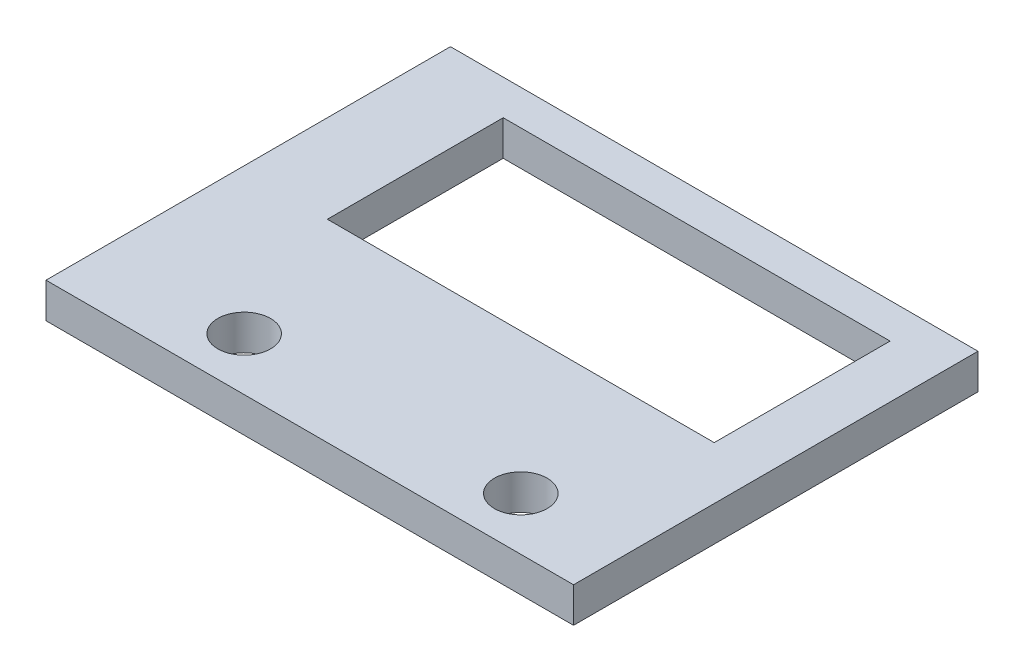
SolidWorks part; units mm, degrees
material "Perspex (TM) GS Acrylic Cast Sheet"
ref_plane "Front Plane" through (0, 0, 0) normal (0, 0, 1) x (1, 0, 0)
ref_plane "Top Plane" through (0, 0, 0) normal (0, 1, 0) x (1, 0, 0)
ref_plane "Right Plane" through (0, 0, 0) normal (1, 0, 0) x (0, 0, -1)
sketch "Sketch1" plane through (0, 0, 0) normal (0, 1, 0) x (1, 0, 0)
  line L1 (15, -11.5) -> (-15, -11.5)
  line L2 (15, -11.5) -> (15, 11.5)
  line L3 (15, 11.5) -> (-15, 11.5)
  line L4 (-15, -11.5) -> (-15, 11.5)
  line L5 (15, -11.5) -> (-15, 11.5) construction
  line L6 (15, 11.5) -> (-15, -11.5) construction
  point P0 (0, 0)
  dimension "D1" = 23
  dimension "D2" = 30
extrude "Boss-Extrude1" add sketch "Sketch1" along normal blind 2
sketch "Sketch3" plane through (0, 2, 0) normal (0, 1, 0) x (1, 0, 0)
  line L1 (15, -11.5) -> (15, 11.5) construction
  line L2 (12, -0.5) -> (-10, -0.5)
  line L4 (-15, -11.5) -> (15, -11.5) construction
  line L10 (12, -0.5) -> (12, 9.5)
  line L11 (12, 9.5) -> (-10, 9.5)
  line L16 (-10, -0.5) -> (-10, 9.5)
  line L17 (12, -0.5) -> (-10, 9.5) construction
  line L18 (12, 9.5) -> (-10, -0.5) construction
  circle A6 centre (-6.73, -8.5) radius 1.5
  circle A7 centre (9, -8.5) radius 1.5
  point P4 (1, 4.5)
  dimension "D1" = 15.73
  dimension "D2" = 3
  dimension "D3" = 3
  dimension "D6" = 6
  dimension "D7" = 10
  dimension "D11" = 3
  dimension "D12" = 3
  dimension "D4" = 11
  dimension "D5" = 3
  dimension "D8" = 22
extrude "Cut-Extrude2" cut sketch "Sketch3" against normal blind 3
